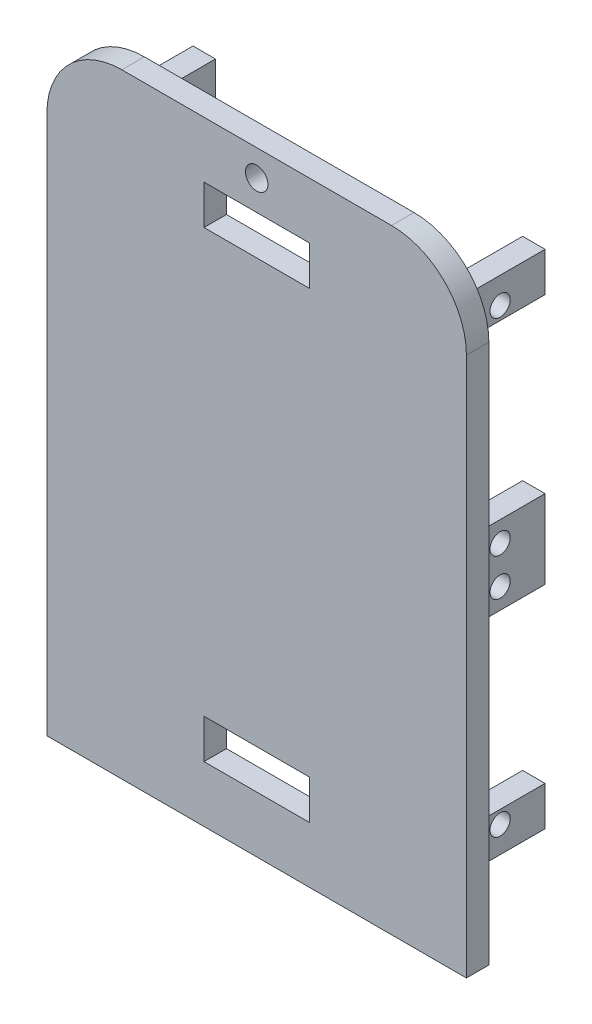
SolidWorks part; units mm, degrees
ref_plane "前视基准面" through (0, 0, 0) normal (0, 0, 1) x (1, 0, 0)
ref_plane "上视基准面" through (0, 0, 0) normal (0, 1, 0) x (1, 0, 0)
ref_plane "右视基准面" through (0, 0, 0) normal (1, 0, 0) x (0, 0, -1)
sketch "草图1" plane through (0, 0, 0) normal (0, 0, 1) x (1, 0, 0)
  line L1 (24, -33.5) -> (-24, -33.5)
  line L2 (24, -33.5) -> (24, 33.5)
  line L3 (24, 33.5) -> (-24, 33.5)
  line L4 (-24, -33.5) -> (-24, 33.5)
  line L5 (24, -33.5) -> (-24, 33.5) construction
  line L6 (24, 33.5) -> (-24, -33.5) construction
  point P0 (0, 0)
  dimension "D1" = 48
  dimension "D2" = 67
extrude "凸台-拉伸2" add sketch "草图1" along normal blind 3
sketch "草图3" plane through (0, 0, 0) normal (0, 0, -1) x (-1, 0, 0)
  line L1 (-24, 33.5) -> (24, 33.5) construction
  line L4 (24, -33.5) -> (-24, -33.5) construction
  line L5 (-23.5, 33.5) -> (-20.5, 33.5)
  line L6 (-23.5, 33.5) -> (-23.5, -33.5)
  line L7 (-23.5, -33.5) -> (-20.5, -33.5)
  line L8 (-20.5, 33.5) -> (-20.5, -33.5)
  line L9 (23.5, -33.4959) -> (20.5, -33.4959)
  line L10 (20.5, 33.5) -> (20.5, -33.4959)
  line L11 (23.5, 33.5) -> (20.5, 33.5)
  line L12 (23.5, 33.5) -> (23.5, -33.4959)
  dimension "D1" = 3
  dimension "D2" = 0.5
  dimension "D3" = 3
  dimension "D4" = 0.5
extrude "凸台-拉伸3" add sketch "草图3" along normal blind 12
sketch "草图4" plane through (23.5, 0, 0) normal (1, 0, 0) x (0, 0, -1)
  line L3 (12, -28.25) -> (0, -28.25)
  line L5 (0, -5.25) -> (0, -28.25)
  line L6 (12, -5.25) -> (0, -5.25)
  line L7 (12, 5.25) -> (0, 5.25)
  line L8 (12, 5.25) -> (12, 28.25)
  line L9 (12, 28.25) -> (0, 28.25)
  line L10 (0, 5.25) -> (0, 28.25)
  line L13 (12, -5.25) -> (12, -28.25)
  circle A0 centre (6, 2.5) radius 1.35
  circle A1 centre (6, 30) radius 1.35
  circle A2 centre (6, -2.5) radius 1.35
  circle A3 centre (6, -30) radius 1.35
  point P18 (6, 16.75)
  dimension "D2" = 2.7
  dimension "D3" = 27.5
extrude "切除-拉伸1" cut sketch "草图4" against normal blind 65
sketch "草图5" plane through (0, 0, 0) normal (0, 0, -1) x (-1, 0, 0)
  line L1 (9.1441, -5.25) -> (-9.1441, -5.25)
  line L2 (9.1441, -5.25) -> (9.1441, 5.25)
  line L3 (9.1441, 5.25) -> (-9.1441, 5.25)
  line L4 (-9.1441, -5.25) -> (-9.1441, 5.25)
  line L5 (9.1441, -5.25) -> (-9.1441, 5.25) construction
  line L6 (9.1441, 5.25) -> (-9.1441, -5.25) construction
  point P0 (0, 0)
extrude "切除-拉伸2" cut sketch "草图5" against normal blind 65
sketch "草图6" plane through (0, 0, 0) normal (0, 0, -1) x (-1, 0, 0)
  line L0 (-24, 33.5) -> (-23.5, 33.5) construction
  line L2 (20.5, -33.5) -> (20.5, 33.5)
  line L4 (-23.75, -33.5) -> (-23.75, 33.5)
  line L7 (-23.75, 33.5) -> (-24, 33.5)
  line L8 (24, -33.5) -> (20.5, -33.5)
  line L9 (24, -33.5) -> (24, 33.5)
  line L10 (24, 33.5) -> (20.5, 33.5)
  line L11 (-24, -33.5) -> (-24, 33.5)
  line L16 (-23.75, -33.5) -> (-24, -33.5)
  point P0 (0, 0)
  point P8 (0, 0)
extrude "切除-拉伸3" cut sketch "草图6" against normal blind 65
sketch "草图7" plane through (0, 0, 3) normal (0, 0, 1) x (1, 0, 0)
  line L30 (-28, 41) -> (-28, -41)
  line L31 (-28, -41) -> (28, -41)
  line L32 (28, -41) -> (28, 41)
  line L33 (28, 41) -> (-28, 41)
extrude "凸台-拉伸4" add sketch "草图7" against normal up to surface (3 mm away) up to face at (0, 0, 0)
sketch "草图9" plane through (0, 0, 0) normal (0, 0, -1) x (-1, 0, 0)
  line L0 (-7.0326, 33.5) -> (7.0326, 33.5)
  line L1 (-7.0326, 33.5) -> (-7.0326, 28.25)
  line L2 (-7.0326, 28.25) -> (7.0326, 28.25)
  line L3 (7.0326, 28.25) -> (7.0326, 33.5)
  line L4 (0, -28.25) -> (-7.0326, -28.25)
  line L5 (-7.0326, -28.25) -> (-7.0326, -33.5)
  line L6 (-7.0326, -33.5) -> (7.0326, -33.5)
  line L7 (7.0326, -33.5) -> (7.0326, -28.25)
  line L8 (7.0326, -28.25) -> (0, -28.25)
  point P3 (0, 33.5)
extrude "切除-拉伸4" cut sketch "草图9" against normal up to surface (3 mm away) up to face at (0, 0, 3)
sketch "草图10" plane through (0, 0, 3) normal (0, 0, 1) x (1, 0, 0)
  circle A0 centre (0, 37.4835) radius 1.5
  dimension "D1" = 3
extrude "切除-拉伸5" cut sketch "草图10" against normal up to surface (3 mm away) up to face at (0, 30.875, 0)
fillet "圆角2" radius 10 2 edges at (28, 41, 1.5) (-28, 41, 1.5)
